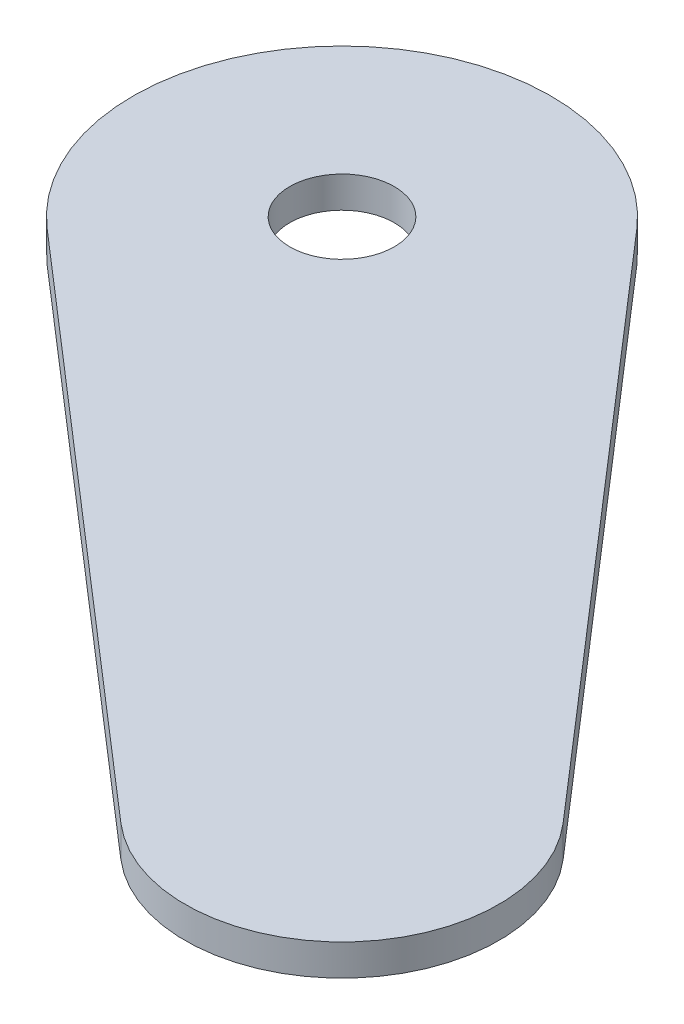
SolidWorks part; units mm, degrees
ref_plane "前视基准面" through (0, 0, 0) normal (0, 0, 1) x (1, 0, 0)
ref_plane "上视基准面" through (0, 0, 0) normal (0, 1, 0) x (1, 0, 0)
ref_plane "右视基准面" through (0, 0, 0) normal (1, 0, 0) x (0, 0, -1)
other "Configuration Table"
sketch "草图1" plane through (0, 0, 0) normal (0, 1, 0) x (1, 0, 0)
  line L0 (0, 0) -> (35.275, 0) construction
  line L1 (0, 0) -> (49.4975, -49.4975) construction
  line L2 (-13.0959, -15.1162) -> (39.6756, -60.8346)
  line L3 (15.1162, 13.0959) -> (60.8346, -39.6756)
  circle A0 centre (0, 0) radius 20
  circle A1 centre (49.4975, -49.4975) radius 15
  dimension "D1" = 40
  dimension "D3" = 30
  dimension "D2" = 70
extrude "凸台-拉伸1" add sketch "草图1" along normal blind 3 contours A0 | A1 L3 A0 L2 | A1
sketch "草图2" plane through (0, 3, 0) normal (0, 1, 0) x (1, 0, 0)
  circle A0 centre (0, 0) radius 2.5
  dimension "D1" = 5
extrude "切除-拉伸1" cut sketch "草图2" against normal through all
sketch "草图3" plane through (0, 3, 0) normal (0, 1, 0) x (1, 0, 0)
  circle A0 centre (0, 0) radius 5
  dimension "D1" = 10
extrude "切除-拉伸2" cut sketch "草图3" against normal blind 10
